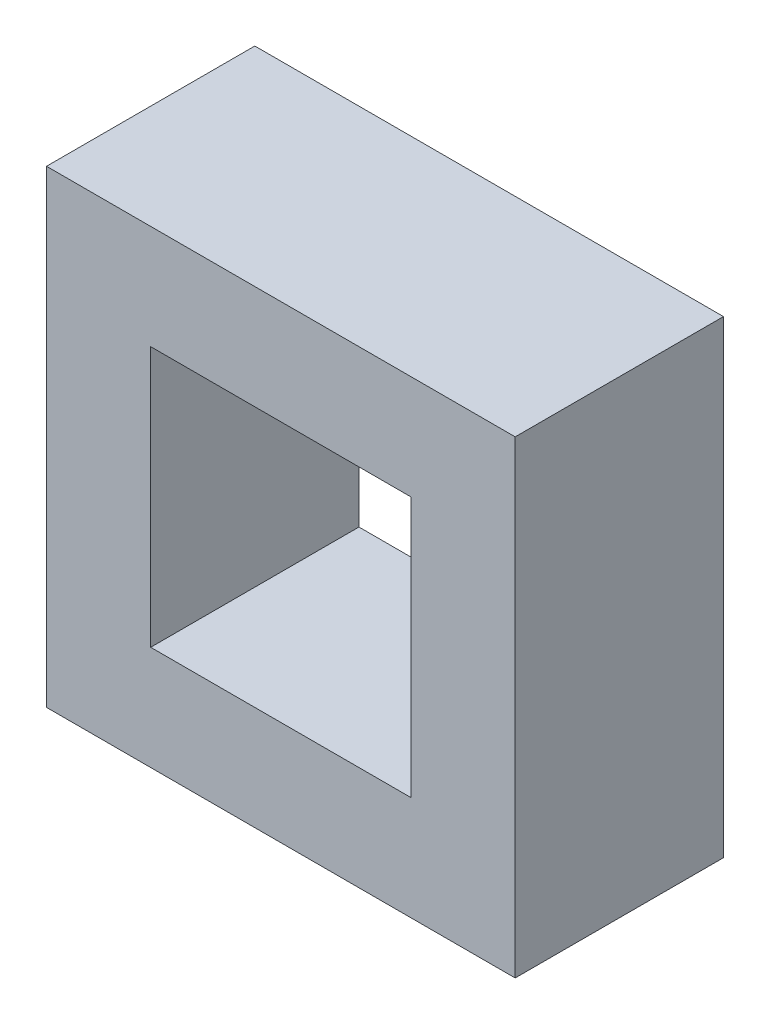
SolidWorks part; units mm, degrees
ref_plane "Front Plane" through (0, 0, 0) normal (0, 0, 1) x (1, 0, 0)
ref_plane "Top Plane" through (0, 0, 0) normal (0, 1, 0) x (1, 0, 0)
ref_plane "Right Plane" through (0, 0, 0) normal (1, 0, 0) x (0, 0, -1)
sketch "Sketch1" plane through (0, 0, 0) normal (0, 0, 1) x (1, 0, 0)
  line L1 (-22.5, -22.5) -> (22.5, -22.5)
  line L2 (-22.5, -22.5) -> (-22.5, 22.5)
  line L3 (-22.5, 22.5) -> (22.5, 22.5)
  line L4 (22.5, -22.5) -> (22.5, 22.5)
  line L5 (-12.5, 12.5) -> (12.5, 12.5)
  line L6 (-12.5, 12.5) -> (-12.5, -12.5)
  line L7 (-12.5, -12.5) -> (12.5, -12.5)
  line L8 (12.5, 12.5) -> (12.5, -12.5)
  point P9 (0, 12.5)
  point P10 (0, 22.5)
  point P11 (-12.5, 0)
  point P12 (-22.5, 0)
  point P13 (0, -22.5)
  dimension "D1" = 25
  dimension "D2" = 45
extrude "Boss-Extrude1" add sketch "Sketch1" along normal blind 20
